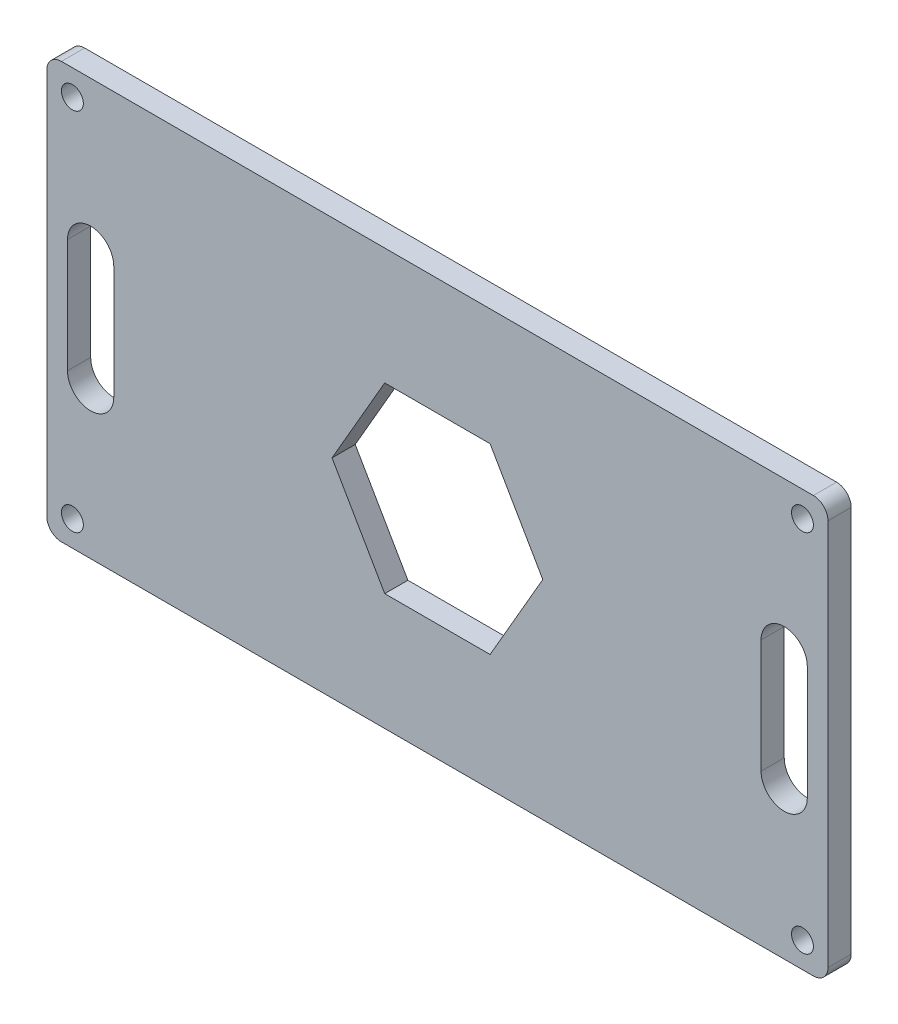
SolidWorks part; units mm, degrees
ref_plane "Front Plane" through (0, 0, 0) normal (0, 0, 1) x (1, 0, 0)
ref_plane "Top Plane" through (0, 0, 0) normal (0, 1, 0) x (1, 0, 0)
ref_plane "Right Plane" through (0, 0, 0) normal (1, 0, 0) x (0, 0, -1)
sketch "Sketch1" plane through (0, 0, 0) normal (0, 0, 1) x (1, 0, 0)
  line L0 (-50, 25) -> (50, -25) construction
  line L1 (-53.5, 28.5) -> (53.5, 28.5)
  line L2 (-53.5, 28.5) -> (-53.5, -28.5)
  line L3 (-53.5, -28.5) -> (53.5, -28.5)
  line L4 (53.5, 28.5) -> (53.5, -28.5)
  line L5 (-50, 25) -> (50, 25) construction
  line L6 (-50, 25) -> (-50, -25) construction
  line L7 (-50, -25) -> (50, -25) construction
  line L8 (50, 25) -> (50, -25) construction
  line L9 (-53.5, -28.5) -> (53.5, 28.5) construction
  circle A0 centre (-50, 25) radius 1.5
  circle A1 centre (50, 25) radius 1.5
  circle A2 centre (-50, -25) radius 1.5
  circle A3 centre (50, -25) radius 1.5
  point P8 (0, 0)
  point P9 (0, 0)
  dimension "D5" = 3
  dimension "D1" = 107
  dimension "D2" = 57
  dimension "D3" = 50
  dimension "D4" = 100
extrude "Boss-Extrude1" add sketch "Sketch1" along normal blind 3.175
fillet "Fillet1" radius 2 4 edges at (-53.5, -28.5, 1.5875) (53.5, -28.5, 1.5875) (53.5, 28.5, 1.5875) (-53.5, 28.5, 1.5875)
sketch "Sketch2" plane through (0, 0, 3.175) normal (0, 0, 1) x (1, 0, 0)
  line L0 (47.5, -7.7872) -> (47.5, 7.7872) construction
  line L1 (44.3323, -7.7872) -> (44.3323, 7.7872)
  line L2 (50.6677, -7.7872) -> (50.6677, 7.7872)
  line L3 (-47.5, -7.7872) -> (-47.5, 7.7872) construction
  line L4 (-50.6677, -7.7872) -> (-50.6677, 7.7872)
  line L5 (-44.3323, -7.7872) -> (-44.3323, 7.7872)
  line L6 (-47.5, 0) -> (-53.5, 0) construction
  line L7 (47.5, 0) -> (53.5, 0) construction
  line L8 (-53.5, 26.5) -> (-53.5, -26.5) construction
  line L9 (53.5, -26.5) -> (53.5, 26.5) construction
  line L11 (14.4338, 0) -> (7.2169, 12.5)
  line L12 (7.2169, 12.5) -> (-7.2169, 12.5)
  line L13 (-7.2169, 12.5) -> (-14.4338, 0)
  line L14 (-14.4338, 0) -> (-7.2169, -12.5)
  line L15 (-7.2169, -12.5) -> (7.2169, -12.5)
  line L16 (7.2169, -12.5) -> (14.4338, 0)
  arc A0 (44.3323, -7.7872) -> (50.6677, -7.7872) centre (47.5, -7.7872) ccw
  arc A1 (50.6677, 7.7872) -> (44.3323, 7.7872) centre (47.5, 7.7872) ccw
  arc A2 (-50.6677, -7.7872) -> (-44.3323, -7.7872) centre (-47.5, -7.7872) ccw
  arc A3 (-44.3323, 7.7872) -> (-50.6677, 7.7872) centre (-47.5, 7.7872) ccw
  circle A4 centre (0, 0) radius 12.5 construction
  point P2 (47.5, 0)
  point P9 (-47.5, 0)
  point P20 (-53.5, 0)
  point P23 (53.5, 0)
  dimension "D3" = 25
  dimension "D1" = 6
  dimension "D2" = 15.5743
extrude "Cut-Extrude1" cut sketch "Sketch2" against normal blind 3.175
